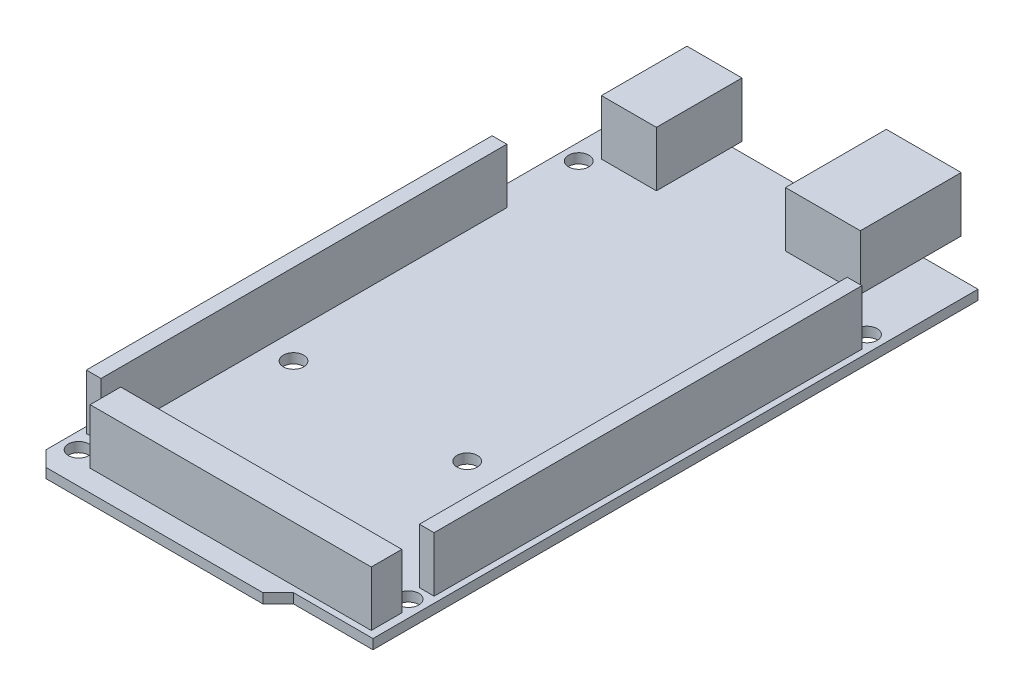
SolidWorks part; units mm, degrees
ref_plane "Front Plane" through (0, 0, 0) normal (0, 0, 1) x (1, 0, 0)
ref_plane "Top Plane" through (0, 0, 0) normal (0, 1, 0) x (1, 0, 0)
ref_plane "Right Plane" through (0, 0, 0) normal (1, 0, 0) x (0, 0, -1)
sketch "Sketch1" plane through (0, 0, 0) normal (0, 1, 0) x (1, 0, 0)
  line L0 (2.5, -2.5) -> (38, -2.5)
  line L1 (0, 0) -> (53.5, 0)
  line L2 (0, 0) -> (0, 99)
  line L3 (0, 99) -> (53.5, 99)
  line L4 (53.5, 0) -> (53.5, 99)
  line L5 (38, -2.5) -> (40.5, 0)
  line L6 (40.5, 0) -> (0, 0)
  line L7 (2.5, -2.5) -> (0, 0)
  circle A0 centre (2.6667, 84.5) radius 1.6667
  circle A1 centre (50.8333, 83.5) radius 1.6667
  circle A2 centre (7.6667, 32.8333) radius 1.6667
  circle A3 centre (36.0833, 32.8333) radius 1.6667
  circle A4 centre (2.6667, 2.6667) radius 1.6667
  circle A5 centre (50.8333, 8.5) radius 1.6667
  dimension "D7" = 14.5
  dimension "D8" = 3.3333
  dimension "D10" = 2.6667
  dimension "D11" = 15.5
  dimension "D12" = 2.6667
  dimension "D14" = 8.5
  dimension "D15" = 2.6667
  dimension "D16" = 17.4167
  dimension "D17" = 7.6667
  dimension "D18" = 66.1667
  dimension "D19" = 66.1667
  dimension "D1" = 53.5
  dimension "D2" = 99
  dimension "D3" = 45
  dimension "D4" = 45
  dimension "D5" = 101.5
  dimension "D6" = 35.5
  dimension "D9" = 2.6667
  dimension "D13" = 2.6667
extrude "Boss-Extrude1" add sketch "Sketch1" along normal blind 1.6 contours L1 L4 L3 L2 A5 A4 A3 A2 A1 A0 | L7 L0 L5 L1
sketch "Sketch2" plane through (0, 1.6, 0) normal (0, 1, 0) x (1, 0, 0)
  line L0 (53.5, 0) -> (53.5, 99) construction
  line L1 (6.22, 1) -> (52.22, 1)
  line L2 (6.22, 1) -> (6.22, 6)
  line L3 (6.22, 6) -> (52.22, 6)
  line L4 (52.22, 1) -> (52.22, 6)
  line L5 (1, 5.6) -> (3.4, 5.6)
  line L6 (1, 5.6) -> (1, 72)
  line L7 (1, 72) -> (3.4, 72)
  line L8 (3.4, 5.6) -> (3.4, 72)
  line L9 (50.1, 11) -> (52.5, 11)
  line L10 (50.1, 11) -> (50.1, 81)
  line L11 (50.1, 81) -> (52.5, 81)
  line L12 (52.5, 11) -> (52.5, 81)
  line L13 (4.25, 86.63) -> (13.25, 86.63)
  line L14 (32.34, 88.66) -> (44.59, 88.66)
  line L15 (32.34, 88.66) -> (32.34, 105.16)
  line L16 (32.34, 105.16) -> (44.59, 105.16)
  line L17 (44.59, 88.66) -> (44.59, 105.16)
  line L18 (4.25, 86.63) -> (4.25, 100.63)
  line L19 (4.25, 100.63) -> (13.25, 100.63)
  line L20 (13.25, 86.63) -> (13.25, 100.63)
  line L21 (40.5, 0) -> (53.5, 0) construction
  line L22 (0, 0) -> (0, 99) construction
  line L23 (0, 99) -> (53.5, 99) construction
  point P20 (51.3, 81)
  point P21 (51.3, 11)
  point P22 (2.2, 5.6)
  dimension "D1" = 2.4
  dimension "D2" = 2.4
  dimension "D3" = 70
  dimension "D4" = 66.4
  dimension "D5" = 46
  dimension "D6" = 5
  dimension "D7" = 1
  dimension "D8" = 1
  dimension "D9" = 1
  dimension "D10" = 6.22
  dimension "D11" = 18
  dimension "D12" = 27
  dimension "D13" = 16.5
  dimension "D14" = 12.25
  dimension "D15" = 9
  dimension "D16" = 14
  dimension "D17" = 4.25
  dimension "D18" = 1.63
  dimension "D19" = 6.16
  dimension "D20" = 8.91
extrude "Boss-Extrude2" add sketch "Sketch2" along normal blind 9
